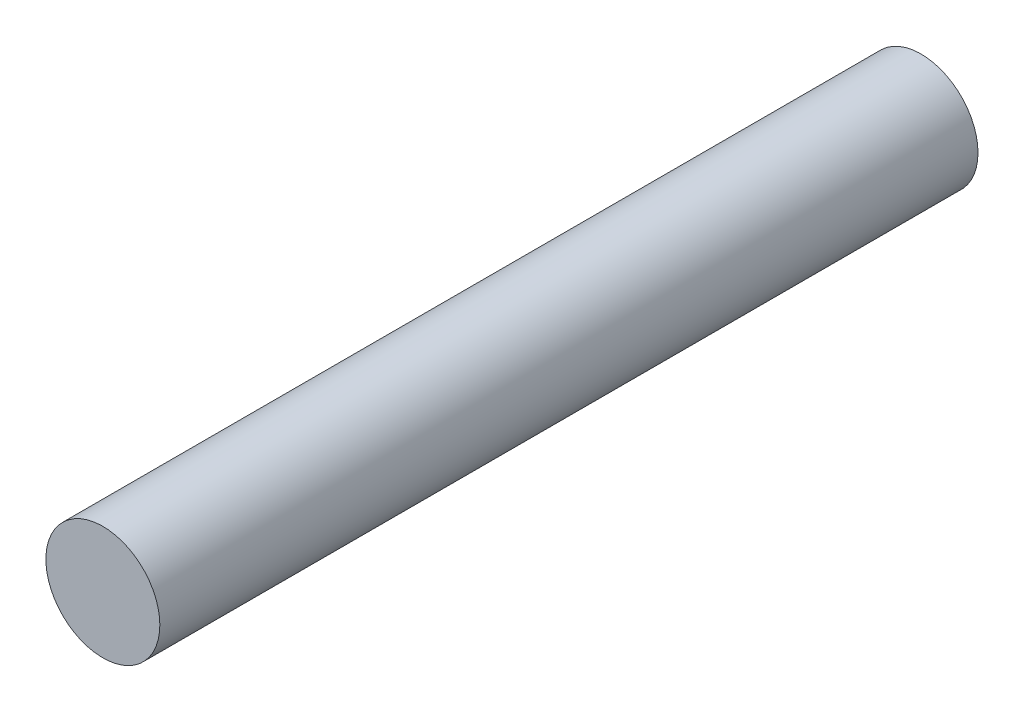
SolidWorks part; units mm, degrees
material "6061-T6 (SS)"
ref_plane "Front Plane" through (0, 0, 0) normal (0, 0, 1) x (1, 0, 0)
ref_plane "Top Plane" through (0, 0, 0) normal (0, 1, 0) x (1, 0, 0)
ref_plane "Right Plane" through (0, 0, 0) normal (1, 0, 0) x (0, 0, -1)
sketch "Body sketch" plane through (0, 0, 0) normal (0, 0, 1) x (1, 0, 0)
  circle A0 centre (0, 0) radius 2.5
extrude "Body" add sketch "Body sketch" along normal blind 35.9
